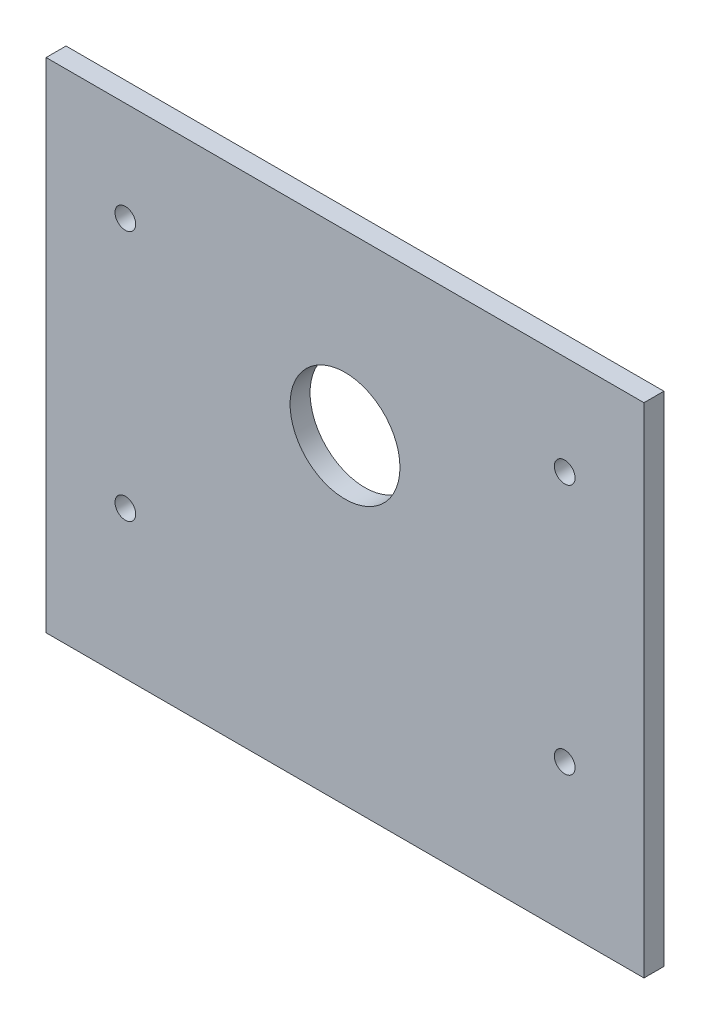
SolidWorks part; units mm, degrees
ref_plane "Front Plane" through (0, 0, 0) normal (0, 0, 1) x (1, 0, 0)
ref_plane "Top Plane" through (0, 0, 0) normal (0, 1, 0) x (1, 0, 0)
ref_plane "Right Plane" through (0, 0, 0) normal (1, 0, 0) x (0, 0, -1)
sketch "Sketch1" plane through (0, 0, 0) normal (0, 0, 1) x (1, 0, 0)
  line L0 (-28, 19.05) -> (-38.1, 19.05) construction
  line L1 (-38.1, -31.75) -> (38.1, -31.75)
  line L2 (-38.1, -31.75) -> (-38.1, 31.75)
  line L3 (-38.1, 31.75) -> (38.1, 31.75)
  line L4 (38.1, -31.75) -> (38.1, 31.75)
  line L5 (-38.1, -31.75) -> (38.1, 31.75) construction
  line L6 (-38.1, 31.75) -> (38.1, -31.75) construction
  line L7 (28, 19.05) -> (38.1, 19.05) construction
  circle A0 centre (-28, 19.05) radius 1.3208
  circle A1 centre (28, 19.05) radius 1.3208
  circle A2 centre (-28, -12.95) radius 1.3208
  circle A3 centre (28, -12.95) radius 1.3208
  circle A4 centre (0, 9.05) radius 7
  point P0 (0, 0)
  point P16 (-38.1, 18.9353)
  point P18 (-38.1, 17.451)
  dimension "D6" = 14
  dimension "D7" = 2.6416
  dimension "D1" = 76.2
  dimension "D2" = 63.5
  dimension "D3" = 56
  dimension "D4" = 32
  dimension "D5" = 10
  dimension "D8" = 12.7
extrude "Boss-Extrude1" add sketch "Sketch1" against normal blind 2.54
